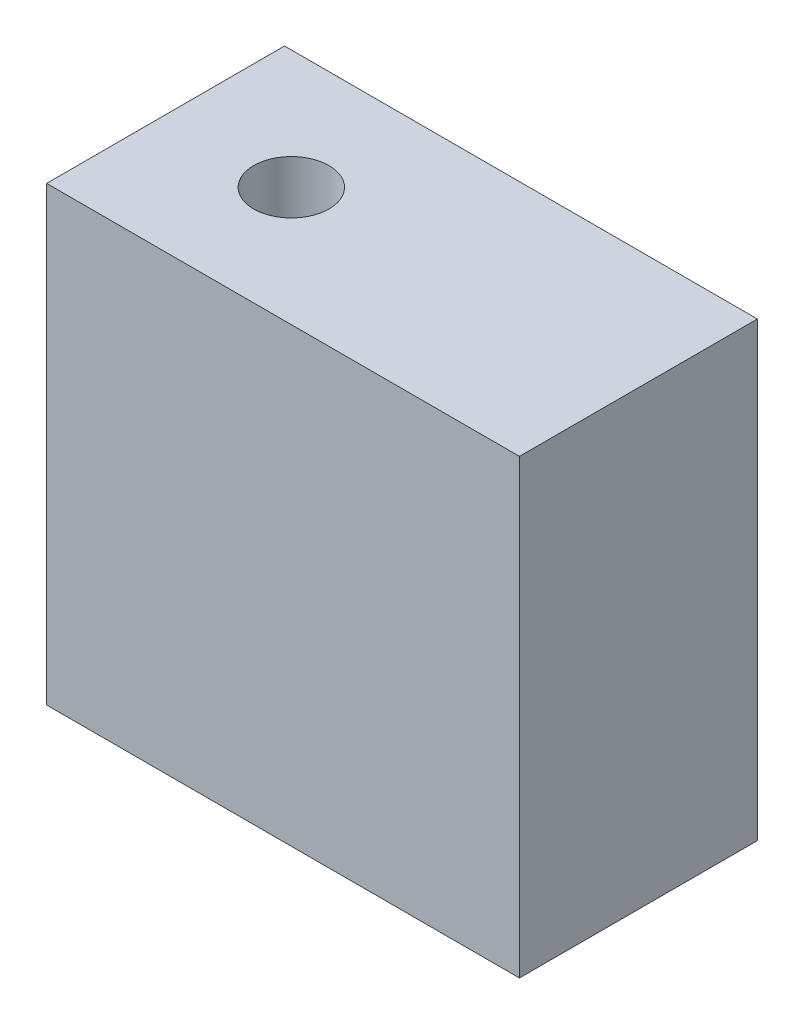
SolidWorks part; units mm, degrees
ref_plane "Front Plane" through (0, 0, 0) normal (0, 0, 1) x (1, 0, 0)
ref_plane "Top Plane" through (0, 0, 0) normal (0, 1, 0) x (1, 0, 0)
ref_plane "Right Plane" through (0, 0, 0) normal (1, 0, 0) x (0, 0, -1)
sketch "Sketch1" plane through (0, 0, 0) normal (0, 1, 0) x (1, 0, 0)
  line L1 (0, 0) -> (-39.878, 0)
  line L2 (0, 0) -> (0, -20.066)
  line L3 (0, -20.066) -> (-39.878, -20.066)
  line L4 (-39.878, 0) -> (-39.878, -20.066)
  dimension "D1" = 39.878
  dimension "D2" = 20.066
extrude "Boss-Extrude1" add sketch "Sketch1" along normal blind 38.1
sketch "Sketch2" plane through (0, 38.1, 0) normal (0, 1, 0) x (1, 0, 0)
  line L0 (-39.878, -20.066) -> (-29.2735, -20.066) construction
  line L1 (-39.878, -20.066) -> (0, -20.066) construction
  line L2 (-29.2735, -20.066) -> (-29.2735, 0) construction
  line L3 (0, 0) -> (-39.878, 0) construction
  circle A0 centre (-29.2735, -10.033) radius 3.175
  dimension "D1" = 6.35
extrude "Cut-Extrude1" cut sketch "Sketch2" against normal blind 12.7
